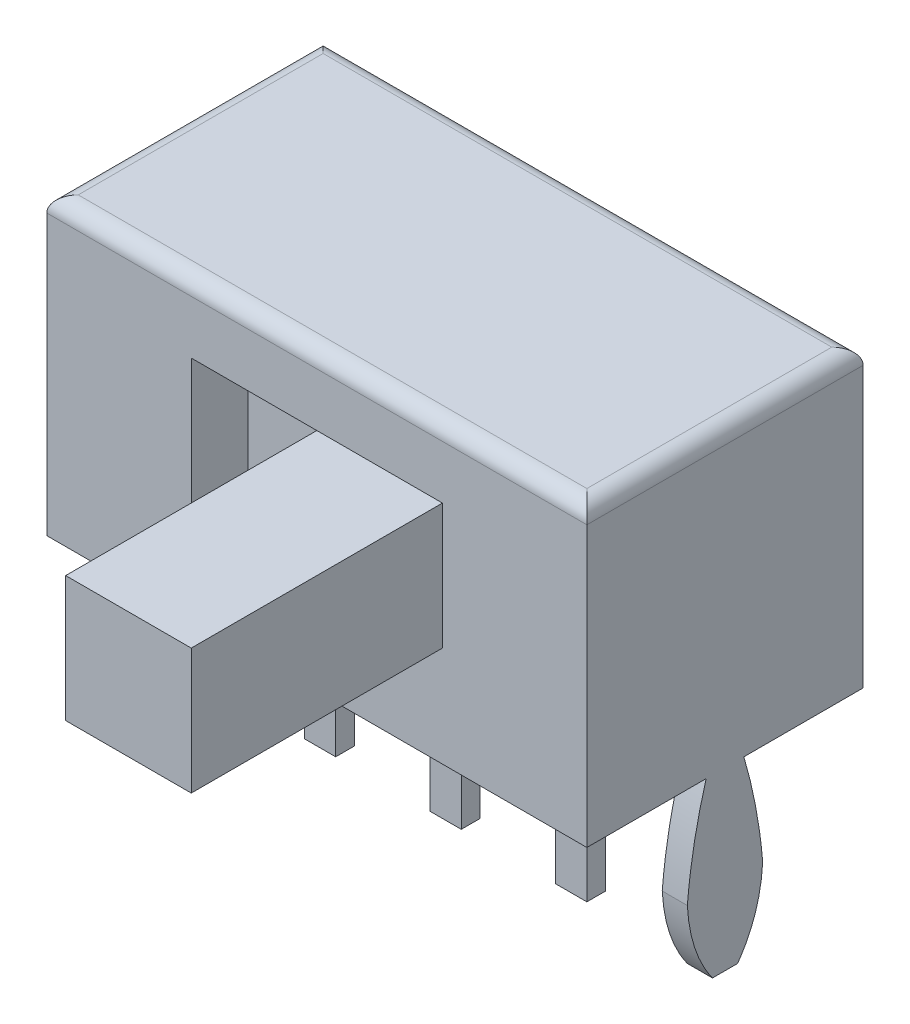
SolidWorks part; units mm, degrees
ref_plane "Front Plane" through (0, 0, 0) normal (0, 0, 1) x (1, 0, 0)
ref_plane "Top Plane" through (0, 0, 0) normal (0, 1, 0) x (1, 0, 0)
ref_plane "Right Plane" through (0, 0, 0) normal (1, 0, 0) x (0, 0, -1)
sketch "Sketch1" plane through (0, 0, 0) normal (0, 1, 0) x (1, 0, 0)
  line L1 (0, 0) -> (8.6, 0)
  line L2 (0, 0) -> (0, -4.4)
  line L3 (0, -4.4) -> (8.6, -4.4)
  line L4 (8.6, 0) -> (8.6, -4.4)
  dimension "D1" = 8.6
  dimension "D2" = 4.4
extrude "Boss-Extrude1" add sketch "Sketch1" against normal blind 4.7
sketch "Sketch4" plane through (0, 0, 4.4) normal (0, 0, 1) x (1, 0, 0)
  line L0 (4.3, -4.7) -> (4.3, -1.1) construction
  line L1 (0, -4.7) -> (8.6, -4.7) construction
  line L2 (4.3, -1.1) -> (2.3, -1.1) construction
  line L3 (0, -4.7) -> (0, 0) construction
  line L4 (2.3, -1.1) -> (6.3, -1.1)
  line L5 (2.3, -1.1) -> (2.3, -3.1)
  line L6 (2.3, -3.1) -> (6.3, -3.1)
  line L7 (6.3, -1.1) -> (6.3, -3.1)
  dimension "D1" = 4
  dimension "D2" = 2
  dimension "D3" = 3.6
  dimension "D4" = 2.3
extrude "Cut-Extrude1" cut sketch "Sketch4" against normal blind 0.9 contours L7 L6 L5 L4
sketch "Sketch5" plane through (0, 0, 3.5) normal (0, 0, 1) x (1, 0, 0)
  line L0 (2.3, -3.1) -> (6.3, -3.1) construction
  line L1 (4.3, -3.1) -> (6.3, -3.1)
  line L2 (4.3, -3.1) -> (4.3, -1.1)
  line L3 (4.3, -1.1) -> (6.3, -1.1)
  line L4 (6.3, -3.1) -> (6.3, -1.1)
extrude "Boss-Extrude3" add sketch "Sketch5" along normal blind 4.9
sketch "Sketch7" plane through (0, -4.7, 0) normal (0, -1, 0) x (1, 0, 0)
  line L0 (0, 0) -> (0, 4.4) construction
  line L1 (0, 4.4) -> (0, 2.8) construction
  line L2 (4.3, 4.4) -> (4.3, 0) construction
  line L3 (0, 2.8) -> (0.4, 2.8)
  line L4 (0, 2.8) -> (0, 1.6)
  line L5 (0, 1.6) -> (0.4, 1.6)
  line L6 (0.4, 2.8) -> (0.4, 1.6)
  line L7 (0, 4.4) -> (8.6, 4.4) construction
  line L8 (8.6, 0) -> (0, 0) construction
  line L9 (8.6, 1.6) -> (8.2, 1.6)
  line L10 (8.2, 2.8) -> (8.2, 1.6)
  line L11 (8.6, 2.8) -> (8.2, 2.8)
  line L12 (8.6, 2.8) -> (8.6, 1.6)
  dimension "D1" = 1.6
  dimension "D2" = 1.2
  dimension "D3" = 0.4
extrude "Boss-Extrude4" add sketch "Sketch7" along normal blind 2.8
sketch "Sketch8" plane through (0, 0, 0) normal (-1, 0, 0) x (0, 0, 1)
  line L0 (2.2, -7.5) -> (2.2, -4.7) construction
  line L1 (2.8, -7.5) -> (1.6, -7.5) construction
  line L2 (1.6, -4.7) -> (1.9, -4.7)
  line L3 (1.6, -4.7) -> (1.6, -7.5)
  line L4 (1.6, -7.5) -> (2, -7.5)
  line L5 (1.6, -7.5) -> (1.6, -6.3) construction
  line L6 (2.8, -7.5) -> (2.4, -7.5)
  line L7 (2.8, -4.7) -> (2.5, -4.7)
  line L8 (2.8, -7.5) -> (2.8, -6.3) construction
  line L9 (2.8, -4.7) -> (2.8, -7.5)
  spline S0 degree 2 poles (1.9, -4.7) (1.6679, -5.4924) (1.6, -6.3) knots 0 0 0 0.54757 0.54757 0.54757
  spline S1 degree 2 poles (1.6, -6.3) (1.6382, -6.9975) (2, -7.5) knots 0 0 0 0.682369 0.682369 0.682369
  spline S2 degree 2 poles (2.8, -6.3) (2.7618, -6.9975) (2.4, -7.5) knots 0 0 0 0.682369 0.682369 0.682369
  spline S3 degree 2 poles (2.5, -4.7) (2.7321, -5.4924) (2.8, -6.3) knots 0 0 0 0.54757 0.54757 0.54757
  point P6 (0, 0)
  point P8 (1.6, -6.3)
  point P18 (2.8, -6.3)
  line M4 (1.6, -4.7) -> (1.6, -7.5)
  line M5 (1.6, -7.5) -> (2.8, -7.5)
  line M6 (2.8, -7.5) -> (2.8, -4.7)
  dimension "D4" = 1.2826
  dimension "D1" = 2.8
  dimension "D2" = 1.2
  dimension "D3" = 0.3
extrude "Cut-Extrude3" cut sketch "Sketch8" against normal blind 8.6 contours S0 L2 M4 | L7 S3 L9 | S2 M6 M5 | S1 L3 M5
sketch "Sketch9" plane through (0, -4.7, 0) normal (0, -1, 0) x (1, 0, 0)
  line L0 (2.05, 2.2) -> (2.05, 2.35) construction
  line L1 (0, 2.4) -> (0, 2) construction
  line L2 (4.05, 2.35) -> (4.05, 2.05)
  line L3 (0, 2.2) -> (2.05, 2.2) construction
  line L4 (2.05, 2.35) -> (2.55, 2.35)
  line L5 (2.05, 2.35) -> (2.05, 2.05)
  line L6 (2.05, 2.05) -> (2.55, 2.05)
  line L7 (2.55, 2.35) -> (2.55, 2.05)
  line L8 (4.05, 2.35) -> (4.55, 2.35)
  line L9 (4.55, 2.35) -> (4.55, 2.05)
  line L10 (4.05, 2.05) -> (4.55, 2.05)
  line L11 (6.05, 2.35) -> (6.05, 2.05)
  line L12 (6.05, 2.35) -> (6.55, 2.35)
  line L13 (6.55, 2.35) -> (6.55, 2.05)
  line L14 (6.05, 2.05) -> (6.55, 2.05)
  line L15 (8.6, 4.4) -> (8.6, 2.5) construction
  dimension "D1" = 2.05
  dimension "D2" = 0.15
  dimension "D3" = 0.5
  dimension "D4" = 0.3
  dimension "D6" = 2.05
  dimension "D5" = 3
extrude "Boss-Extrude5" add sketch "Sketch9" along normal blind 2.8
fillet "Fillet1" radius 0.25 4 edges at (4.3, 0, 0) (8.6, 0, 2.2) (4.3, 0, 4.4) (0, 0, 2.2)
